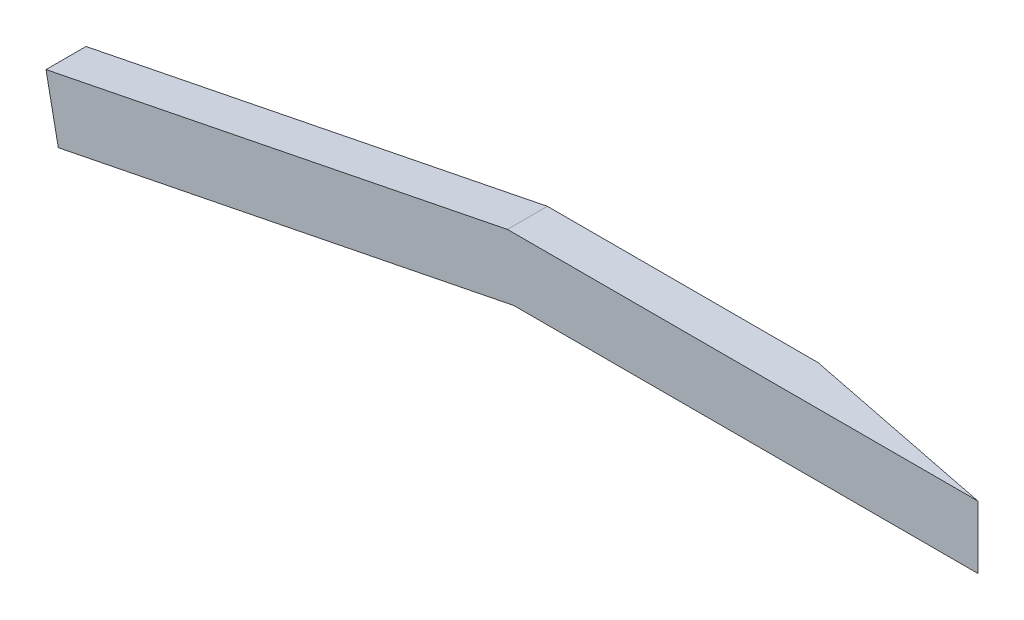
SolidWorks part; units mm, degrees
ref_plane "Front Plane" through (0, 0, 0) normal (0, 0, 1) x (1, 0, 0)
ref_plane "Top Plane" through (0, 0, 0) normal (0, 1, 0) x (1, 0, 0)
ref_plane "Right Plane" through (0, 0, 0) normal (1, 0, 0) x (0, 0, -1)
sketch "Sketch1" plane through (0, 0, 0) normal (0, 1, 0) x (1, 0, 0)
  line L0 (-1.8787, -1.397) -> (-1.8787, -0.1223)
  line L1 (-1.8787, -0.1223) -> (6.7475, -0.1223)
  line L5 (6.7475, -0.1223) -> (13.1213, -1.397)
  line L6 (13.1213, -1.397) -> (-1.8787, -1.397)
extrude "Boss-Extrude2" add sketch "Sketch1" along normal blind 2
sketch "Sketch4" plane through (0, 0, 1.397) normal (0, 0, 1) x (1, 0, 0)
  line L0 (-1.8787, 2) -> (-16.5874, -0.9417)
  line L1 (-16.5874, -0.9417) -> (-16.1952, -2.9029)
  line L2 (-16.1952, -2.9029) -> (-1.4865, 0.0388)
  line L3 (-1.8787, 2) -> (-1.4865, 0.0388)
extrude "Boss-Extrude4" add sketch "Sketch4" against normal up to vertex (1.2748 mm away)
